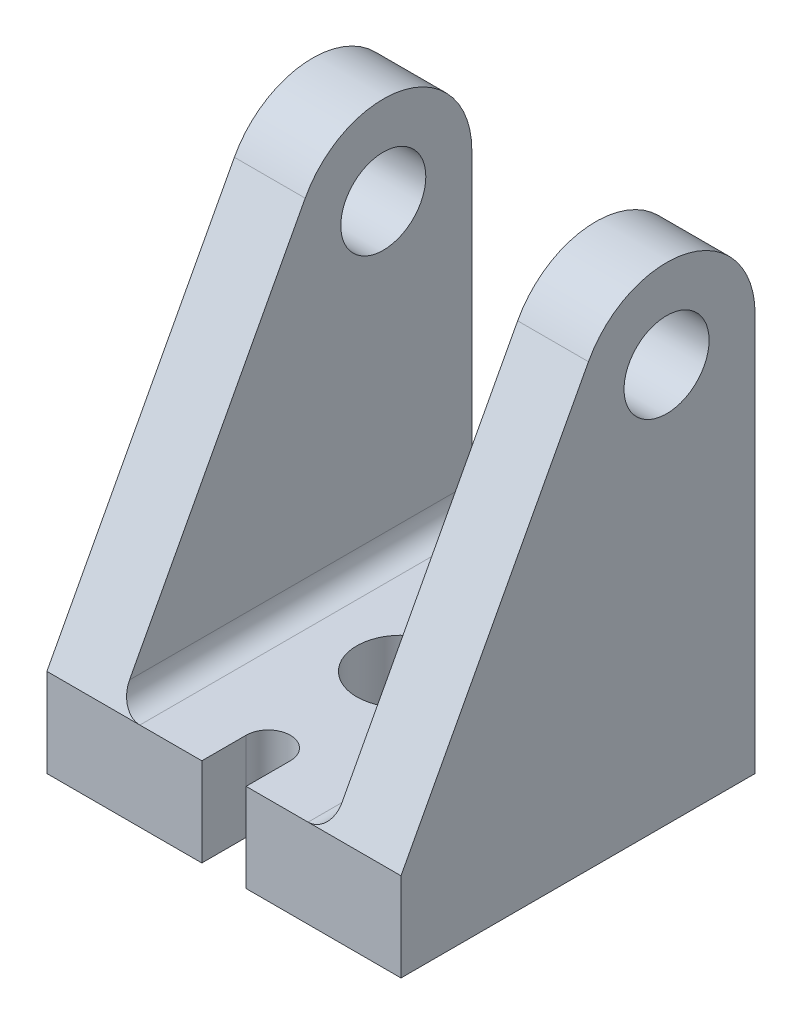
SolidWorks part; units mm, degrees
ref_plane "Front Plane" through (0, 0, 0) normal (0, 0, 1) x (1, 0, 0)
ref_plane "Top Plane" through (0, 0, 0) normal (0, 1, 0) x (1, 0, 0)
ref_plane "Right Plane" through (0, 0, 0) normal (1, 0, 0) x (0, 0, -1)
sketch "Sketch1" plane through (0, 0, 0) normal (0, 1, 0) x (1, 0, 0)
  line L0 (-25.4, 25.4) -> (25.4, -25.4) construction
  line L1 (-25.4, 25.4) -> (25.4, 25.4)
  line L2 (-25.4, 25.4) -> (-25.4, -25.4)
  line L3 (-25.4, -25.4) -> (25.4, -25.4)
  line L4 (25.4, 25.4) -> (25.4, -25.4)
  dimension "D1" = 50.8
  dimension "D2" = 50.8
extrude "Boss-Extrude1" add sketch "Sketch1" along normal blind 12.7
sketch "Sketch2" plane through (25.4, 0, 0) normal (1, 0, 0) x (0, 0, -1)
  line L0 (-25.4, 0) -> (-25.4, 12.7)
  line L1 (-25.4, 12.7) -> (1.4941, 63.1265)
  line L2 (25.4, 57.15) -> (25.4, 0)
  line L3 (25.4, 0) -> (-25.4, 0)
  arc A0 (1.4941, 63.1265) -> (25.4, 57.15) centre (12.7, 57.15) cw
  circle A1 centre (12.7, 57.15) radius 6.1
  dimension "D1" = 12.2
  dimension "D2" = 12.7
  dimension "D3" = 57.15
extrude "Boss-Extrude2" add sketch "Sketch2" against normal blind 10.16
mirror "Mirror1" about plane through (0, 0, 0) normal (1, 0, 0) of "Boss-Extrude2"
sketch "Sketch4" plane through (0, 12.7, 0) normal (0, 1, 0) x (1, 0, 0)
  line L0 (15.24, 25.4) -> (-15.24, -25.4) construction
  line L1 (15.24, -25.4) -> (-15.24, 25.4) construction
  line L2 (0, 25.4) -> (0, -25.4) construction
  line L3 (15.24, 25.4) -> (-15.24, 25.4) construction
  line L4 (-15.24, -25.4) -> (15.24, -25.4) construction
  line L7 (15.24, 0) -> (-15.24, 0) construction
  line L8 (15.24, 25.4) -> (15.24, -25.4) construction
  line L9 (-15.24, -25.4) -> (-15.24, 25.4) construction
  point P8 (-7.7174, 12.8624)
  point P17 (7.7174, 12.8624)
  point P33 (7.7174, -12.8624)
  point P34 (-7.7174, -12.8624)
  dimension "D1" = 15
hole_wizard "#4 (0.209) Diameter Hole1" positions "Sketch4" profile "Sketch5" hole size "#4" standard "ANSI Inch"
sketch "Sketch5" plane through (-9.2581, 12.7, 11.802) normal (1, 0, 0) x (0, 0, 1)
  line L0 (0, 0) -> (0, 12.7)
  line L1 (0, 12.7) -> (2.6543, 12.7)
  line L2 (2.6543, 12.7) -> (2.6543, 0)
  line L5 (2.6543, 0) -> (0, 0)
  line L11 (0, -6.35) -> (0, 107.95) construction
  dimension "Thru Hole Dia." = 5.3086
  dimension "Thru Hole Depth" = 12.7
sketch "Sketch3" plane through (0, 12.7, 0) normal (0, 1, 0) x (1, 0, 0)
  line L0 (-3.175, -25.4) -> (-3.175, -19.05)
  line L2 (-15.24, -25.4) -> (15.24, -25.4) construction
  line L3 (3.175, -19.05) -> (3.175, -25.4)
  line L4 (3.175, -25.4) -> (-3.175, -25.4)
  circle A0 centre (0, 0) radius 6.35
  arc A1 (-3.175, -19.05) -> (3.175, -19.05) centre (0, -19.05) cw
  dimension "D1" = 12.7
  dimension "D2" = 3.175
  dimension "D3" = 19.05
extrude "Cut-Extrude1" cut sketch "Sketch3" against normal through all
fillet "Fillet1" radius 3.175 2 edges at (15.24, 12.7, 0) (-15.24, 12.7, 0)
